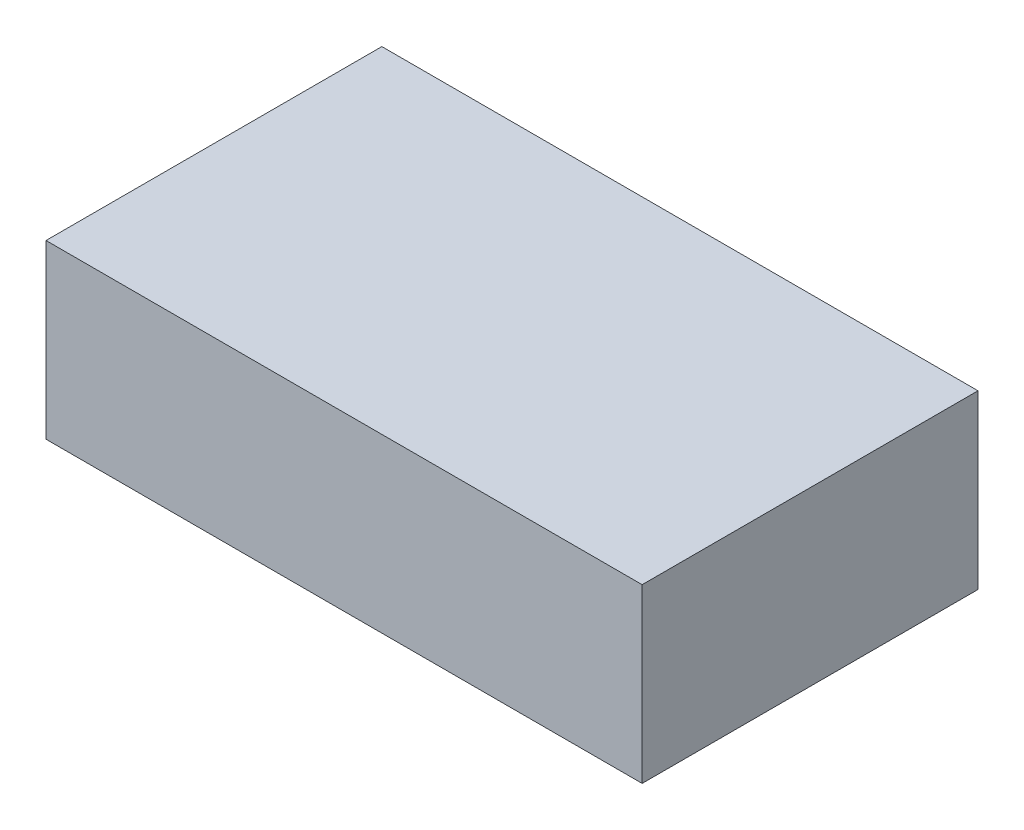
SolidWorks part; units mm, degrees
ref_plane "Front Plane" through (0, 0, 0) normal (0, 0, 1) x (1, 0, 0)
ref_plane "Top Plane" through (0, 0, 0) normal (0, 1, 0) x (1, 0, 0)
ref_plane "Right Plane" through (0, 0, 0) normal (1, 0, 0) x (0, 0, -1)
sketch "Sketch1" plane through (0, 0, 0) normal (0, 1, 0) x (1, 0, 0)
  line L1 (-71, 40) -> (71, 40)
  line L2 (-71, 40) -> (-71, -40)
  line L3 (-71, -40) -> (71, -40)
  line L4 (71, 40) -> (71, -40)
  line L5 (-71, 40) -> (71, -40) construction
  line L6 (-71, -40) -> (71, 40) construction
  point P0 (0, 0)
  dimension "D1" = 142
  dimension "D2" = 80
extrude "Boss-Extrude1" add sketch "Sketch1" along normal blind 41
